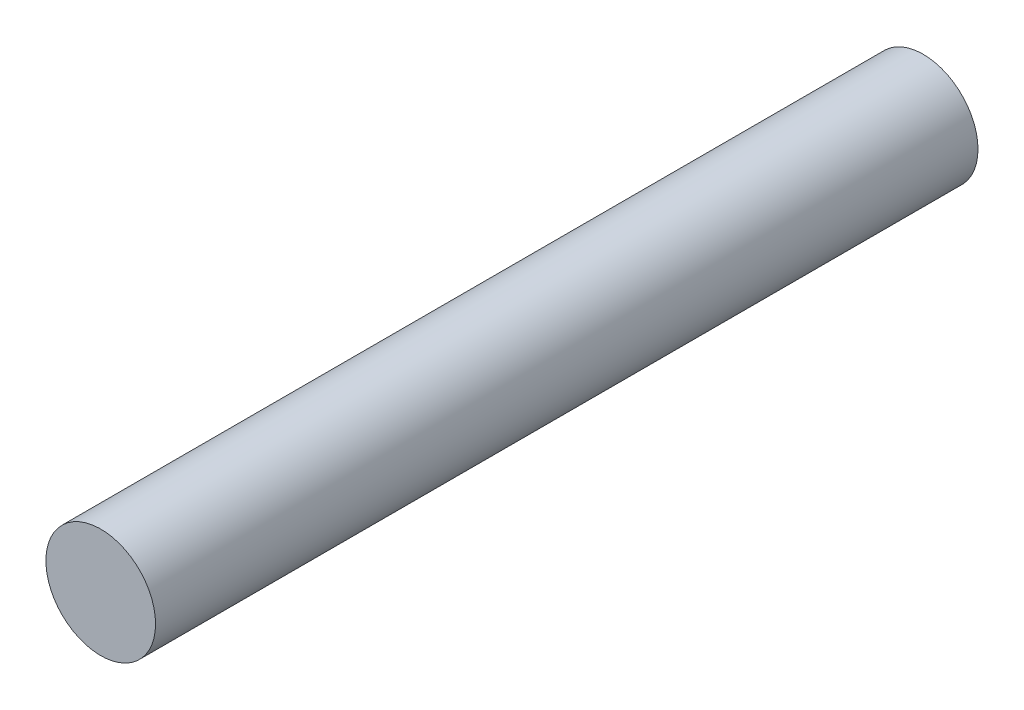
SolidWorks part; units mm, degrees
ref_plane "前视基准面" through (0, 0, 0) normal (0, 0, 1) x (1, 0, 0)
ref_plane "上视基准面" through (0, 0, 0) normal (0, 1, 0) x (1, 0, 0)
ref_plane "右视基准面" through (0, 0, 0) normal (1, 0, 0) x (0, 0, -1)
other "Configuration Table"
sketch "草图1" plane through (0, 0, 0) normal (0, 0, 1) x (1, 0, 0)
  circle A0 centre (0, 0) radius 10
  dimension "D1" = 20
extrude "凸台-拉伸1" add sketch "草图1" along normal blind 150
